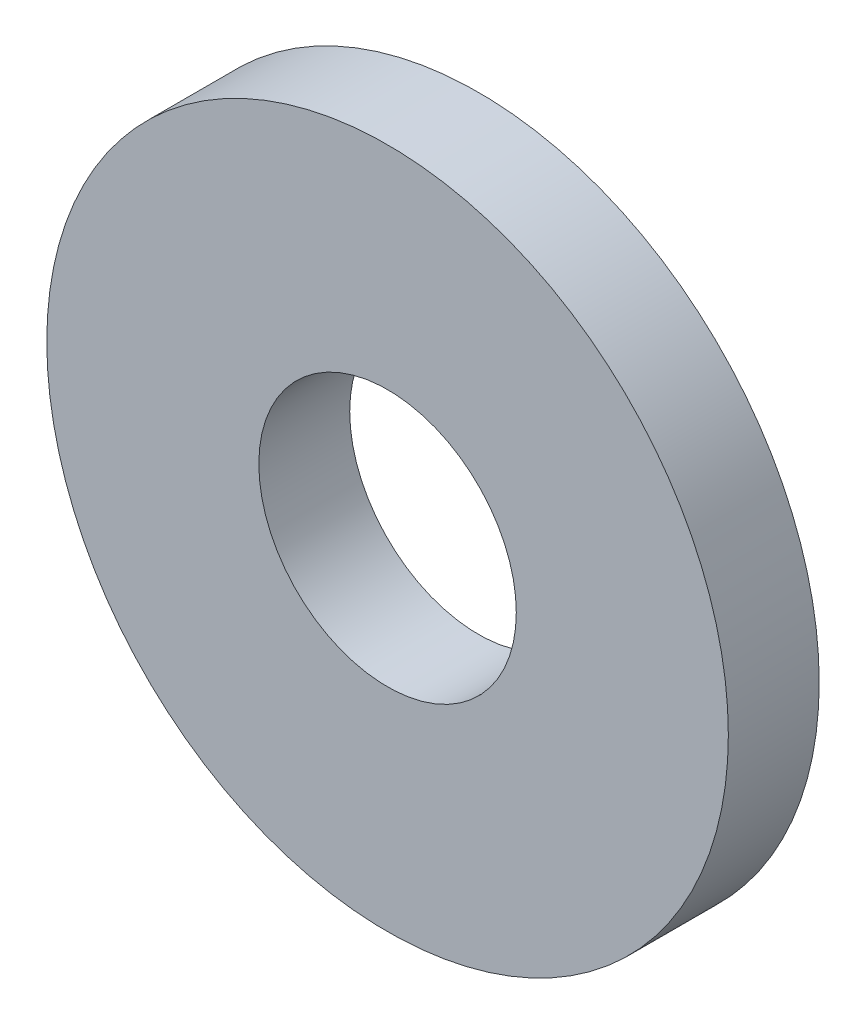
SolidWorks part; units mm, degrees
ref_plane "Front Plane" through (0, 0, 0) normal (0, 0, 1) x (1, 0, 0)
ref_plane "Top Plane" through (0, 0, 0) normal (0, 1, 0) x (1, 0, 0)
ref_plane "Right Plane" through (0, 0, 0) normal (1, 0, 0) x (0, 0, -1)
sketch "Retainer Sketch" plane through (0, 0, 0) normal (0, 0, 1) x (1, 0, 0)
  circle A0 centre (0, 0) radius 4.5
  circle A1 centre (0, 0) radius 1.7
  dimension "D1" = 9
  dimension "D2" = 3.4
extrude "Retainer Extrude" add sketch "Retainer Sketch" along normal blind 1.2 from offset 36.7
equation "\"outside_diameter\"= 9mm 'Retainer outside diameter; contacts the bearing inner race"
equation "\"screw_clearance\"= 3.4mm 'M3 clearance"
equation "\"rear_face_distance\"= 36.7mm 'Rear face measured toward negative motor Z"
equation "\"retainer_thickness\"= 1.2mm 'Retainer thickness"
equation "\"D1@Retainer Sketch\"= \"outside_diameter\""
equation "\"D2@Retainer Sketch\"= \"screw_clearance\""
equation "\"D1@Retainer Extrude\"= \"retainer_thickness\""
equation "\"D19@Retainer Extrude\"= \"rear_face_distance\""
